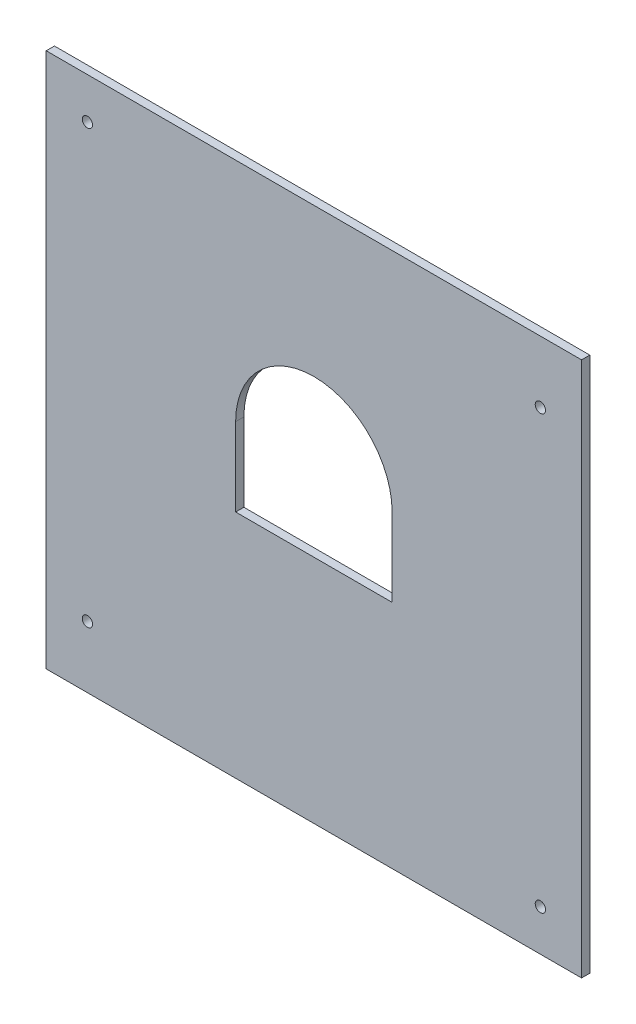
SolidWorks part; units mm, degrees
ref_plane "Спереди" through (0, 0, 0) normal (0, 0, 1) x (1, 0, 0)
ref_plane "Сверху" through (0, 0, 0) normal (0, 1, 0) x (1, 0, 0)
ref_plane "Справа" through (0, 0, 0) normal (1, 0, 0) x (0, 0, -1)
sketch "Эскиз1" plane through (0, 0, 0) normal (0, 0, 1) x (1, 0, 0)
  line L1 (-65, -65) -> (65, -65)
  line L2 (-65, -65) -> (-65, 65)
  line L3 (-65, 65) -> (65, 65)
  line L4 (65, -65) -> (65, 65)
  line L5 (-19, 10) -> (-19, -9)
  line L6 (-19, -9) -> (19, -9)
  line L12 (19, -9) -> (19, 10)
  circle A0 centre (-55, 55) radius 1.25
  circle A1 centre (55, 50) radius 1.25
  circle A2 centre (55, -55) radius 1.25
  circle A3 centre (-55, -50) radius 1.25
  arc A6 (-19, 10) -> (19, 10) centre (0, 10) cw
  dimension "D3" = 2.5
  dimension "D4" = 2.5
  dimension "D5" = 2.5
  dimension "D6" = 2.5
  dimension "D8" = 10
  dimension "D9" = 10
  dimension "D11" = 10
  dimension "D12" = 10
  dimension "D13" = 10
  dimension "D14" = 15
  dimension "D1" = 130
  dimension "D2" = 130
  dimension "D7" = 10
  dimension "D10" = 15
extrude "Бобышка-Вытянуть1" add sketch "Эскиз1" along normal blind 2
